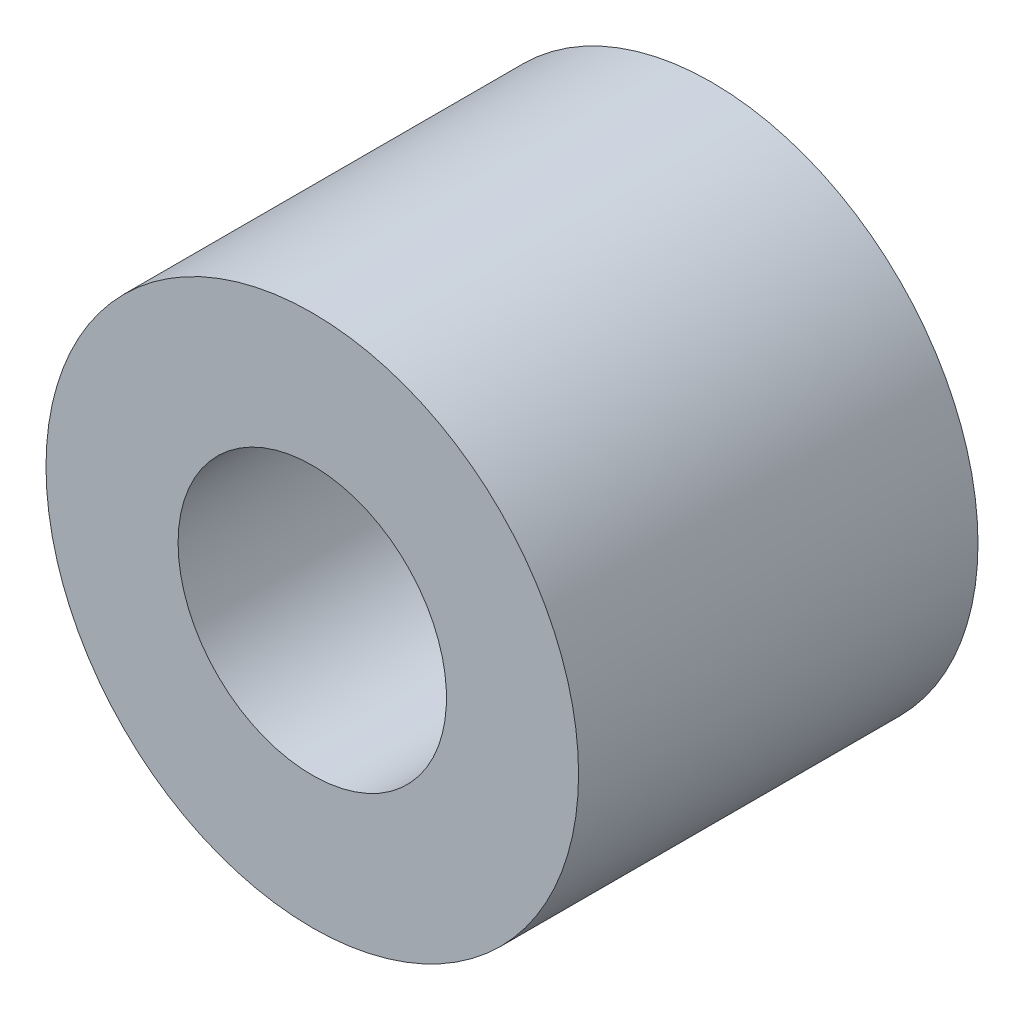
SolidWorks part; units mm, degrees
ref_plane "Front Plane" through (0, 0, 0) normal (0, 0, 1) x (1, 0, 0)
ref_plane "Top Plane" through (0, 0, 0) normal (0, 1, 0) x (1, 0, 0)
ref_plane "Right Plane" through (0, 0, 0) normal (1, 0, 0) x (0, 0, -1)
sketch "Sketch1" plane through (0, 0, 0) normal (0, 0, 1) x (1, 0, 0)
  circle A0 centre (0, 0) radius 6.35
  circle A1 centre (0, 0) radius 3.2004
  dimension "OD" = 12.7
  dimension "ID" = 6.4008
extrude "Extrude1" add sketch "Sketch1" along normal mid plane 9.525
sketch "Sketch2" plane through (0, 0, 0) normal (1, 0, 0) x (0, 0, -1)
  line L0 (-4.7625, -3.2004) -> (4.7625, -3.2004) construction
  line L3 (4.7625, 3.2004) -> (-4.7625, 3.2004) construction
  line L5 (-4.7625, -3.2004) -> (4.7625, -3.2004)
  line L6 (4.7625, 3.2004) -> (-4.7625, 3.2004)
sketch "Sketch4" plane through (0, 0, 4.7625) normal (0, 0, 1) x (1, 0, 0)
  line L0 (0, 0) -> (-2.263, 2.263)
  line L1 (0, -3.4925) -> (0, 3.4925) construction
  circle A0 centre (0, 0) radius 3.2004 construction
  dimension "D1" = 45
